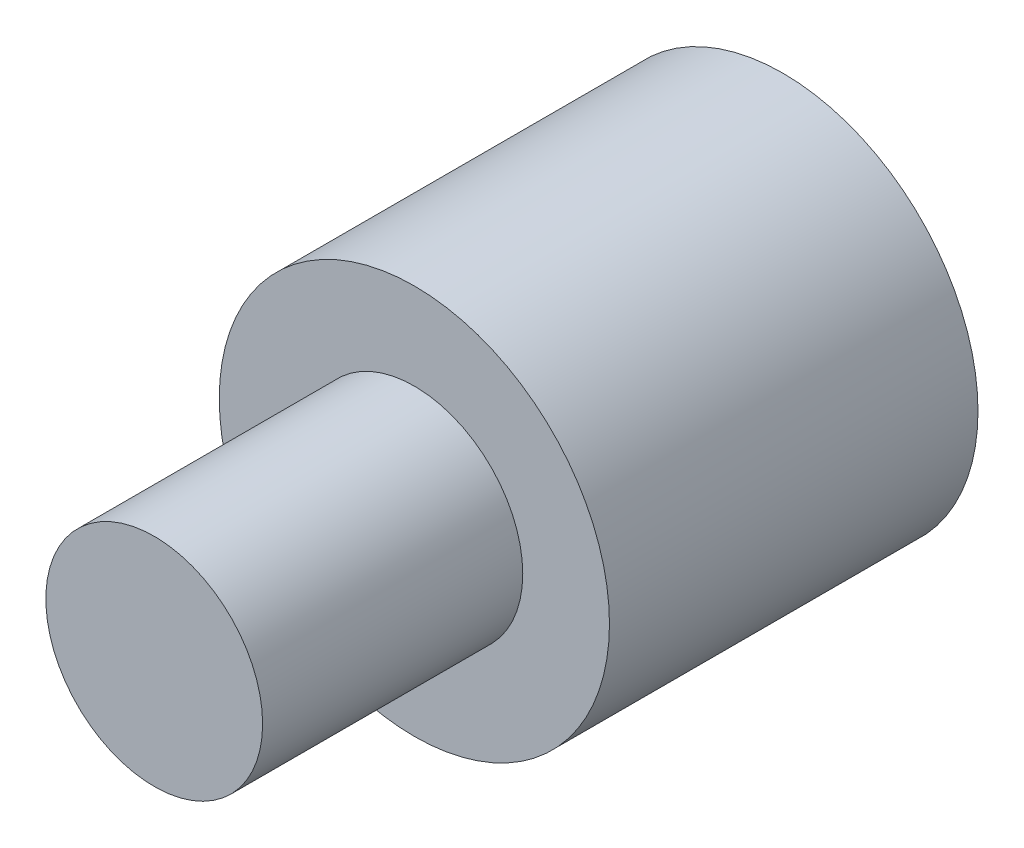
SolidWorks part; units mm, degrees
ref_plane "Alzado" through (0, 0, 0) normal (0, 0, 1) x (1, 0, 0)
ref_plane "Planta" through (0, 0, 0) normal (0, 1, 0) x (1, 0, 0)
ref_plane "Vista lateral" through (0, 0, 0) normal (1, 0, 0) x (0, 0, -1)
sketch "Croquis1" plane through (0, 0, 0) normal (0, 0, 1) x (1, 0, 0)
  circle A0 centre (0, 0) radius 9
  dimension "D1" = 18
extrude "Saliente-Extruir1" add sketch "Croquis1" along normal blind 17
sketch "Croquis2" plane through (0, 0, 17) normal (0, 0, 1) x (1, 0, 0)
  circle A0 centre (0, 0) radius 5
  dimension "D1" = 10
extrude "Saliente-Extruir2" add sketch "Croquis2" along normal blind 12
